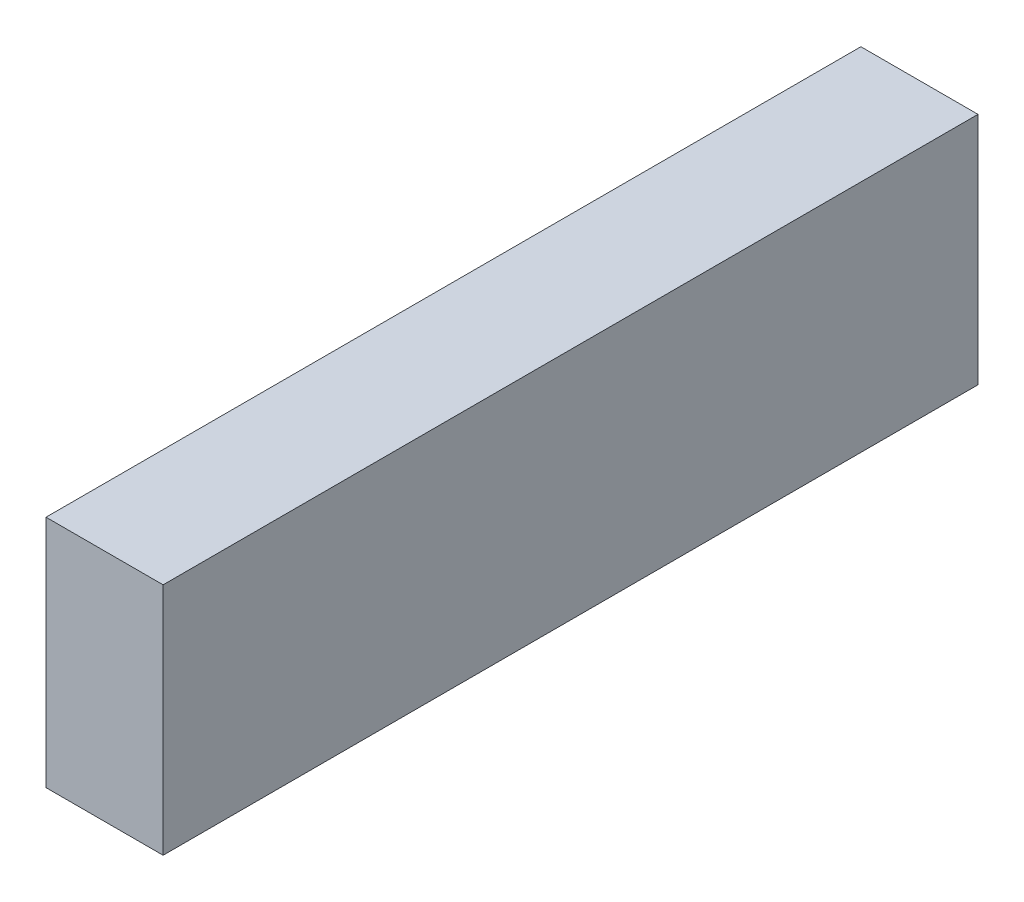
SolidWorks part; units mm, degrees
ref_plane "前视基准面" through (0, 0, 0) normal (0, 0, 1) x (1, 0, 0)
ref_plane "上视基准面" through (0, 0, 0) normal (0, 1, 0) x (1, 0, 0)
ref_plane "右视基准面" through (0, 0, 0) normal (1, 0, 0) x (0, 0, -1)
other "Configuration Table"
sketch "草图1" plane through (0, 0, 0) normal (0, 1, 0) x (1, 0, 0)
  line L1 (-42.3, -17.3) -> (42.3, -17.3)
  line L2 (-42.3, -17.3) -> (-42.3, 17.3)
  line L3 (-42.3, 17.3) -> (42.3, 17.3)
  line L4 (42.3, -17.3) -> (42.3, 17.3)
  line L5 (-42.3, -17.3) -> (42.3, 17.3) construction
  line L6 (-42.3, 17.3) -> (42.3, -17.3) construction
  line L7 (8, -13) -> (22, -13)
  line L8 (8, -13) -> (8, 13)
  line L9 (8, 13) -> (22, 13)
  line L10 (22, -13) -> (22, 13)
  line L11 (8, -13) -> (22, 13) construction
  line L12 (8, 13) -> (22, -13) construction
  line L13 (-32.2857, -8.6923) -> (0, -8.6923)
  line L14 (-32.2857, -8.6923) -> (-32.2857, 8.6923)
  line L15 (-32.2857, 8.6923) -> (0, 8.6923)
  line L16 (0, -8.6923) -> (0, 8.6923)
  line L17 (-32.2857, -8.6923) -> (0, 8.6923) construction
  line L18 (-32.2857, 8.6923) -> (0, -8.6923) construction
  line L19 (-46, -8.6923) -> (0, -8.6923)
  line L20 (-46, -8.6923) -> (-46, 8.6923)
  line L21 (-46, 8.6923) -> (0, 8.6923)
  line L22 (0, -8.6923) -> (0, 8.6923)
  line L23 (-46, -8.6923) -> (0, 8.6923) construction
  line L24 (-46, 8.6923) -> (0, -8.6923) construction
  line L25 (-60, -8.6923) -> (0, -8.6923)
  line L26 (-60, -8.6923) -> (-60, 8.6923)
  line L27 (-60, 8.6923) -> (0, 8.6923)
  line L28 (0, -8.6923) -> (0, 8.6923)
  line L29 (-60, -8.6923) -> (0, 8.6923) construction
  line L30 (-60, 8.6923) -> (0, -8.6923) construction
  point P0 (15, 0)
  point P10 (-16.1429, 0)
  point P15 (-23, 0)
  point P16 (-30, 0)
sketch "草图2" plane through (0, 0, 0) normal (0, 1, 0) x (1, 0, 0)
  line L0 (-42.3, -17.3) -> (42.3, -17.3) construction
  line L1 (40.3, -17.3) -> (42.3, -17.3)
  line L2 (40.3, -17.3) -> (40.3, 17.3)
  line L3 (40.3, 17.3) -> (42.3, 17.3)
  line L4 (42.3, -17.3) -> (42.3, 17.3)
  line L5 (-42.3, -17.3) -> (-42.3, 17.3) construction
  line L6 (-42.3, 15.3) -> (42.3, 15.3)
  line L7 (-42.3, 15.3) -> (-42.3, 17.3)
  line L8 (-42.3, 17.3) -> (42.3, 17.3)
  line L9 (42.3, 15.3) -> (42.3, 17.3)
  line L10 (-42.3, -17.3) -> (42.3, -17.3)
  line L11 (-42.3, -17.3) -> (-42.3, -15.3)
  line L12 (-42.3, -15.3) -> (42.3, -15.3)
  line L13 (42.3, -17.3) -> (42.3, -15.3)
  line L14 (-42.3, 7) -> (-40.3, 7)
  line L15 (-42.3, 7) -> (-42.3, 17.3)
  line L16 (-42.3, 17.3) -> (-40.3, 17.3)
  line L17 (-40.3, 7) -> (-40.3, 17.3)
  line L18 (-46, -8.6923) -> (0, 8.6923) construction
  line L19 (-42.3, -17.3) -> (-41.3, -17.3)
  line L20 (-42.3, -17.3) -> (-42.3, -6.9161)
  line L21 (-42.3, -6.9161) -> (-41.3, -6.9161)
  line L22 (-41.3, -17.3) -> (-41.3, -6.9161)
sketch "草图3" plane through (0, 0, 0) normal (0, 1, 0) x (1, 0, 0)
  line L1 (-42.3, -6.9161) -> (-40.3, -6.9161)
  line L2 (-42.3, -6.9161) -> (-42.3, 7)
  line L3 (-42.3, 7) -> (-40.3, 7)
  line L4 (-40.3, -6.9161) -> (-40.3, 7)
extrude "凸台-拉伸3" add sketch "草图3" along normal blind 4
